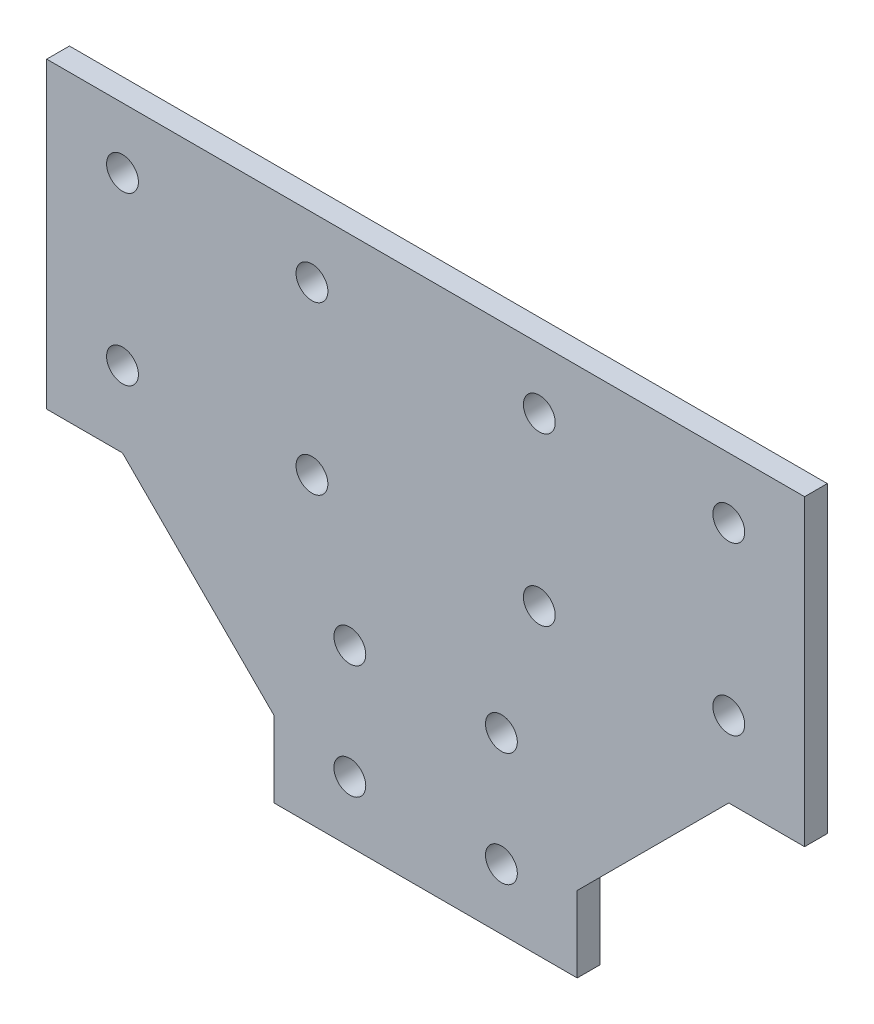
SolidWorks part; units mm, degrees
material "Thornel VCB-20 碳布"
ref_plane "前视基准面" through (0, 0, 0) normal (0, 0, 1) x (1, 0, 0)
ref_plane "上视基准面" through (0, 0, 0) normal (0, 1, 0) x (1, 0, 0)
ref_plane "右视基准面" through (0, 0, 0) normal (1, 0, 0) x (0, 0, -1)
other "Configuration Table"
sketch "草图1" plane through (0, 0, 0) normal (0, 0, 1) x (1, 0, 0)
  line L0 (-20, 0) -> (-30, 0)
  line L1 (-30, 0) -> (-30, 40)
  line L2 (-30, 40) -> (70, 40)
  line L3 (70, 40) -> (70, 0)
  line L4 (70, 0) -> (60, 0)
  line L5 (40, -20) -> (40, -30)
  line L6 (40, -30) -> (0, -30)
  line L7 (0, -30) -> (0, -20)
  line L8 (-20, 0) -> (0, -20)
  line L9 (40, -20) -> (60, 0)
  line L10 (40, -20) -> (40, 0) construction
  line L11 (40, 0) -> (60, 0) construction
  line L12 (-20, 0) -> (0, 0) construction
  line L13 (0, 0) -> (0, -20)
  dimension "D1" = 40
  dimension "D2" = 40
  dimension "D3" = 45
  dimension "D4" = 45
  dimension "D5" = 30
  dimension "D6" = 30
  dimension "D7" = 30
  dimension "D8" = 20
  dimension "D9" = 20
extrude "凸台-拉伸1" add sketch "草图1" along normal blind 3
sketch "草图2" plane through (0, 0, 3) normal (0, 0, 1) x (1, 0, 0)
  line L0 (10, -7) -> (30, -7) construction
  line L1 (30, -7) -> (30, -22) construction
  line L2 (30, -22) -> (10, -22) construction
  line L3 (10, -22) -> (10, -7) construction
  line L4 (-20, 10) -> (60, 10) construction
  line L5 (60, 10) -> (60, 32) construction
  line L6 (60, 32) -> (-20, 32) construction
  line L7 (-20, 32) -> (-20, 10) construction
  line L10 (-20, 0) -> (0, -20)
  line L11 (0, -20) -> (0, -30)
  line L12 (0, -30) -> (40, -30)
  line L13 (40, -30) -> (40, -20)
  line L14 (40, -20) -> (60, 0)
  line L15 (60, 0) -> (70, 0)
  line L16 (70, 0) -> (70, 40)
  line L17 (70, 40) -> (-30, 40)
  line L18 (-30, 40) -> (-30, 0)
  line L19 (-30, 0) -> (-20, 0)
  line L20 (-20, 0) -> (0, -20) construction
  line L21 (0, -20) -> (0, -30) construction
  line L22 (0, -30) -> (40, -30) construction
  line L23 (40, -30) -> (40, -20) construction
  line L24 (40, -20) -> (60, 0) construction
  line L25 (60, 0) -> (70, 0) construction
  line L26 (70, 0) -> (70, 40) construction
  line L27 (70, 40) -> (-30, 40) construction
  line L28 (-30, 40) -> (-30, 0) construction
  line L29 (-30, 0) -> (-20, 0) construction
  circle A0 centre (10, -7) radius 2.1
  circle A1 centre (30, -7) radius 2.1
  circle A2 centre (10, -22) radius 2.1
  circle A3 centre (30, -22) radius 2.1
  circle A4 centre (-20, 10) radius 2.1
  circle A5 centre (-20, 32) radius 2.1
  circle A6 centre (5, 10) radius 2.1
  circle A7 centre (35, 10) radius 2.1
  circle A8 centre (60, 10) radius 2.1
  circle A9 centre (60, 32) radius 2.1
  circle A10 centre (35, 32) radius 2.1
  circle A11 centre (5, 32) radius 2.1
  dimension "D2" = 4.2
  dimension "D3" = 20
  dimension "D4" = 10
  dimension "D5" = 8
  dimension "D6" = 15
  dimension "D7" = 10
  dimension "D8" = 10
  dimension "D9" = 8
  dimension "D10" = 10
  dimension "D11" = 25
  dimension "D12" = 25
  dimension "D13" = 25
  dimension "D14" = 25
  dimension "D1" = 0
extrude "切除-拉伸1" cut sketch "草图2" against normal blind 3
